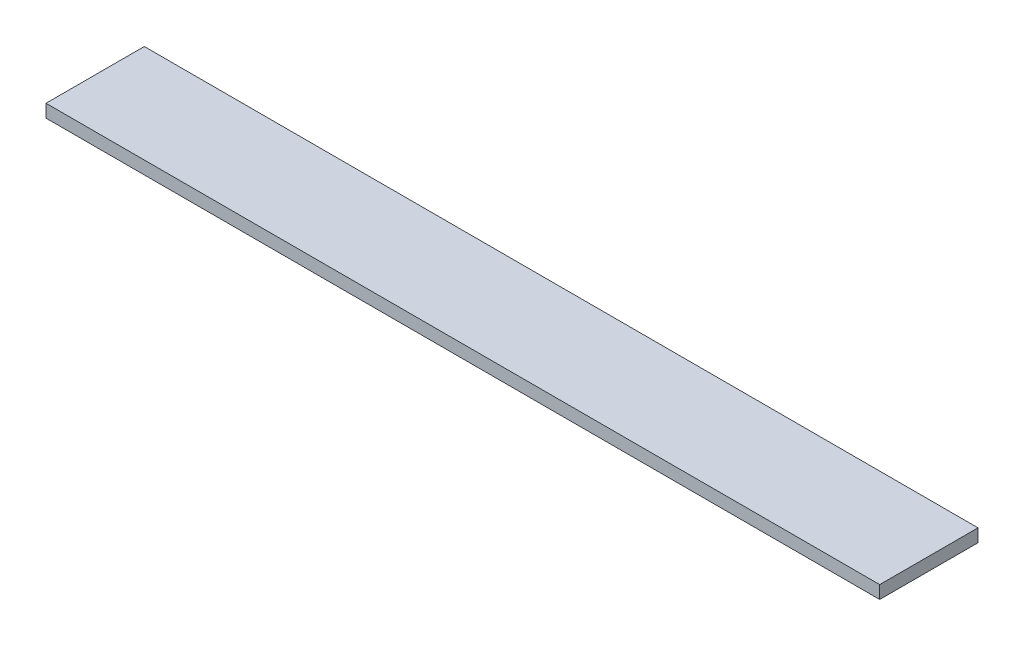
SolidWorks part; units mm, degrees
ref_plane "Front Plane" through (0, 0, 0) normal (0, 0, 1) x (1, 0, 0)
ref_plane "Top Plane" through (0, 0, 0) normal (0, 1, 0) x (1, 0, 0)
ref_plane "Right Plane" through (0, 0, 0) normal (1, 0, 0) x (0, 0, -1)
sketch "Sketch3" plane through (0, 0, 0) normal (0, 1, 0) x (1, 0, 0)
  line L1 (-322.5, -38.0236) -> (322.5, -38.0236)
  line L2 (-322.5, -38.0236) -> (-322.5, 38.0236)
  line L3 (-322.5, 38.0236) -> (322.5, 38.0236)
  line L4 (322.5, -38.0236) -> (322.5, 38.0236)
  line L5 (-322.5, -38.0236) -> (322.5, 38.0236) construction
  line L6 (-322.5, 38.0236) -> (322.5, -38.0236) construction
  point P0 (0, 0)
extrude "Boss-Extrude1" add sketch "Sketch3" along normal blind 10
